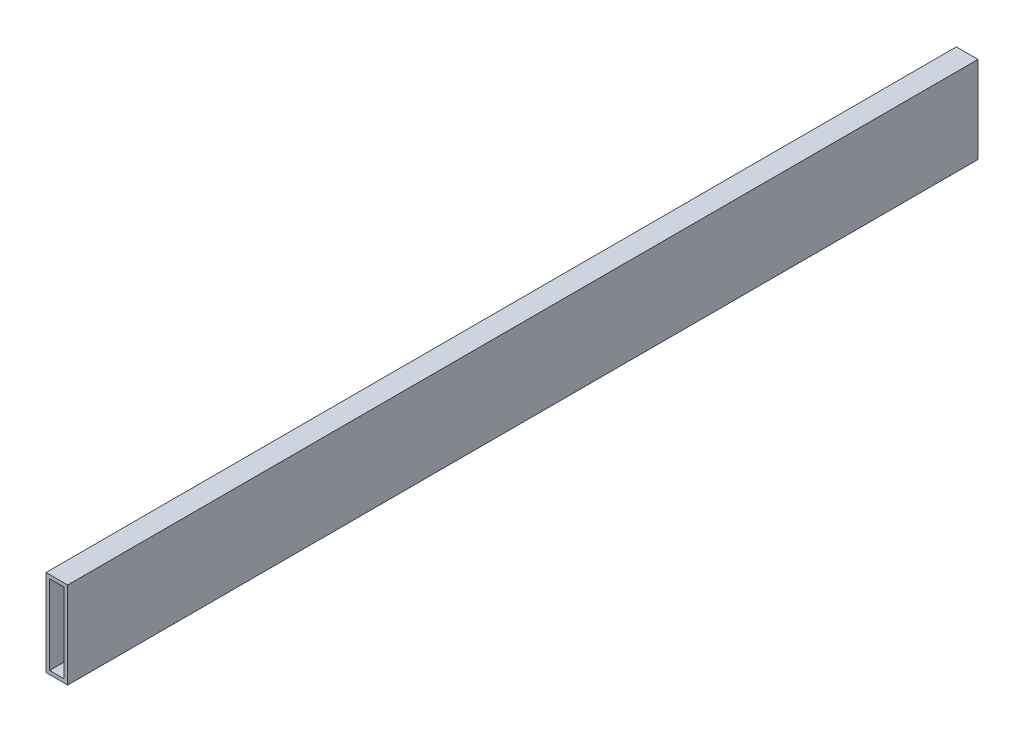
SolidWorks part; units mm, degrees
ref_plane "Front Plane" through (0, 0, 0) normal (0, 0, 1) x (1, 0, 0)
ref_plane "Top Plane" through (0, 0, 0) normal (0, 1, 0) x (1, 0, 0)
ref_plane "Right Plane" through (0, 0, 0) normal (1, 0, 0) x (0, 0, -1)
sketch "Sketch1" plane through (0, 0, 0) normal (0, 0, 1) x (1, 0, 0)
  line L1 (-9.525, -38.1) -> (9.525, -38.1)
  line L2 (-9.525, -38.1) -> (-9.525, 38.1)
  line L3 (-9.525, 38.1) -> (9.525, 38.1)
  line L4 (9.525, -38.1) -> (9.525, 38.1)
  line L5 (-9.525, -38.1) -> (9.525, 38.1) construction
  line L6 (-9.525, 38.1) -> (9.525, -38.1) construction
  point P0 (0, 0)
  dimension "D1" = 76.2
  dimension "D2" = 19.05
extrude "Extrude-Thin1" add sketch "Sketch1" along normal blind 800.1 thin thin type one direction reverse wall 3.175
